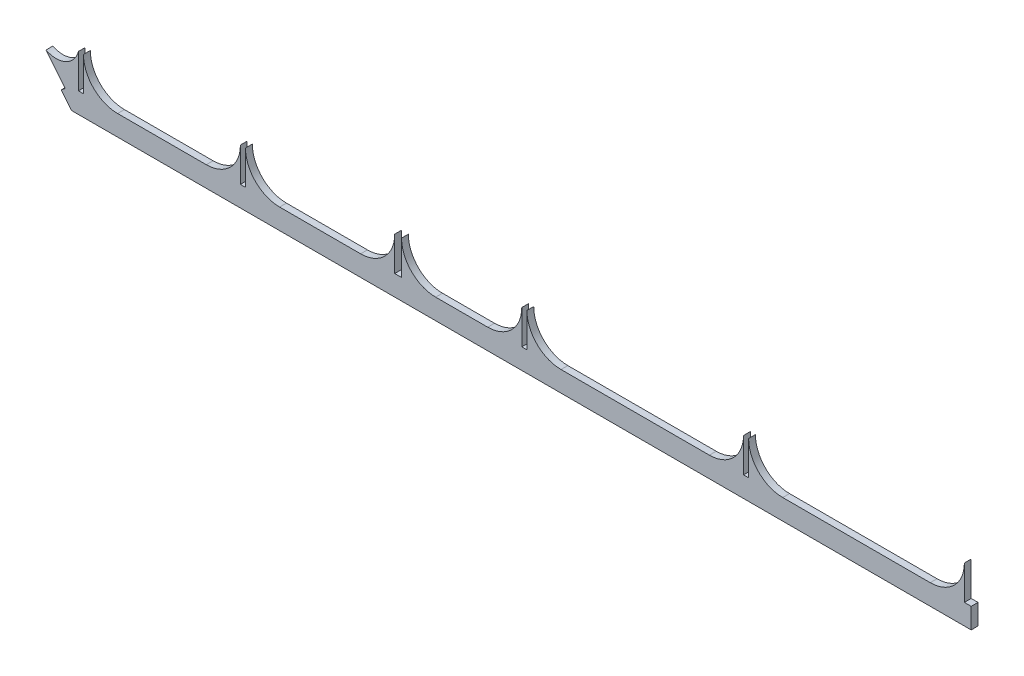
SolidWorks part; units mm, degrees
ref_plane "前视基准面" through (0, 0, 0) normal (0, 0, 1) x (1, 0, 0)
ref_plane "上视基准面" through (0, 0, 0) normal (0, 1, 0) x (1, 0, 0)
ref_plane "右视基准面" through (0, 0, 0) normal (1, 0, 0) x (0, 0, -1)
sketch "Model" plane through (0, 0, 0) normal (0, 0, 1) x (1, 0, 0)
  line L0 (287.6646, 8.035) -> (23.9146, 8.035)
  line L1 (287.6646, 14.035) -> (285.6646, 14.035)
  line L2 (287.6646, 14.035) -> (287.6646, 8.035)
  line L3 (275.6646, 14.035) -> (232.4146, 14.035)
  line L4 (222.4146, 14.035) -> (220.9146, 14.035)
  line L5 (210.9146, 14.035) -> (167.4145, 14.035)
  line L6 (157.4145, 14.035) -> (155.9146, 14.035)
  line L7 (145.9146, 14.035) -> (130.6645, 14.035)
  line L8 (108.6646, 14.035) -> (84.9145, 14.035)
  line L9 (74.9145, 14.035) -> (73.4146, 14.035)
  line L10 (63.4146, 14.035) -> (37.4145, 14.035)
  line L11 (27.4145, 14.035) -> (25.9146, 14.035)
  line L12 (22.0844, 12.7301) -> (20.88, 11.7548)
  line L13 (16.4258, 19.6664) -> (22.0844, 12.7301)
  line L14 (20.88, 11.7548) -> (23.9146, 8.035)
  line L15 (285.6646, 24.035) -> (285.6646, 14.035)
  line L16 (222.4146, 24.035) -> (222.4146, 14.035)
  line L17 (220.9146, 24.035) -> (220.9146, 14.035)
  line L18 (157.4145, 24.035) -> (157.4145, 14.035)
  line L19 (155.9146, 24.035) -> (155.9146, 14.035)
  line L20 (120.6645, 14.035) -> (118.6646, 14.035)
  line L21 (120.6645, 24.035) -> (120.6645, 14.035)
  line L22 (118.6646, 24.035) -> (118.6646, 14.035)
  line L23 (74.9145, 24.035) -> (74.9145, 14.035)
  line L24 (73.4146, 14.035) -> (73.4146, 24.035)
  line L25 (27.4145, 24.035) -> (27.4145, 14.035)
  line L26 (25.9146, 24.035) -> (25.9146, 14.035)
  arc A0 (275.6646, 14.035) -> (285.6646, 24.035) centre (275.6646, 24.035) ccw
  arc A1 (210.9146, 14.035) -> (220.9146, 24.035) centre (210.9146, 24.035) ccw
  arc A2 (145.9146, 14.035) -> (155.9146, 24.035) centre (145.9146, 24.035) ccw
  arc A3 (16.4258, 19.6664) -> (25.9146, 24.035) centre (19.3883, 25.7211) ccw
  arc A4 (222.4146, 24.035) -> (232.4146, 14.035) centre (232.4146, 24.035) ccw
  arc A5 (63.4146, 14.035) -> (73.4146, 24.035) centre (63.4146, 24.035) ccw
  arc A6 (108.6646, 14.035) -> (118.6646, 24.035) centre (108.6646, 24.035) ccw
  arc A7 (74.9145, 24.035) -> (84.9145, 14.035) centre (84.9145, 24.035) ccw
  arc A8 (120.6645, 24.035) -> (130.6645, 14.035) centre (130.6645, 24.035) ccw
  arc A9 (157.4145, 24.035) -> (167.4145, 14.035) centre (167.4145, 24.035) ccw
  arc A10 (27.4145, 24.035) -> (37.4145, 14.035) centre (37.4145, 24.035) ccw
extrude "凸台-拉伸1" add sketch "Model" along normal blind 2
